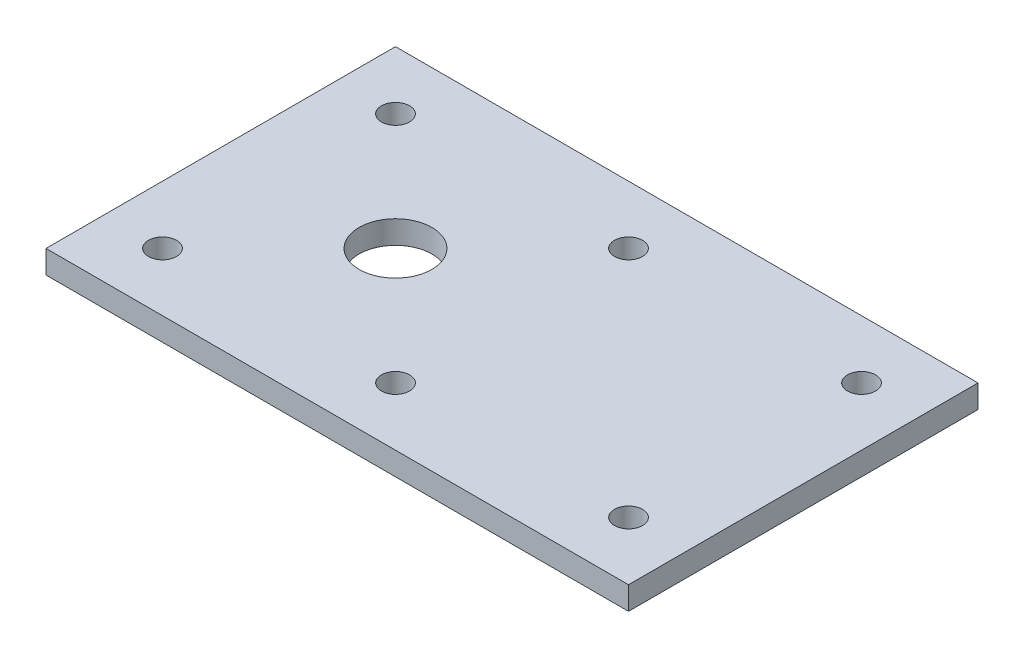
SolidWorks part; units mm, degrees
ref_plane "Front Plane" through (0, 0, 0) normal (0, 0, 1) x (1, 0, 0)
ref_plane "Top Plane" through (0, 0, 0) normal (0, 1, 0) x (1, 0, 0)
ref_plane "Right Plane" through (0, 0, 0) normal (1, 0, 0) x (0, 0, -1)
sketch "Sketch1" plane through (0, 0, 0) normal (0, 1, 0) x (1, 0, 0)
  line L0 (-60, 0) -> (140, 0) construction
  line L1 (-60, 60) -> (140, 60)
  line L2 (-60, 60) -> (-60, -60)
  line L3 (-60, -60) -> (140, -60)
  line L4 (140, 60) -> (140, -60)
  dimension "D1" = 200
  dimension "D2" = 120
  dimension "D3" = 60
extrude "Boss-Extrude1" add sketch "Sketch1" along normal blind 7.9248 contours L2 L1 L4 L3
sketch "Sketch3" plane through (0, 7.9248, 0) normal (0, 1, 0) x (1, 0, 0)
  line L0 (-60, 40) -> (-40, 40) construction
  line L1 (-60, 60) -> (-60, -60) construction
  line L2 (-40, 60) -> (-40, -60) construction
  line L3 (-60, 60) -> (140, 60) construction
  line L4 (-60, -60) -> (140, -60) construction
  line L5 (-40, 40) -> (-40, 60) construction
  line L6 (-40, 40) -> (-40, 60) construction
  line L7 (-40, 40) -> (-44.8013, 40.4875) construction
  line L8 (-40, 40) -> (-44.8152, 40.3229) construction
  circle A0 centre (-40, 40) radius 4.826
  dimension "D1" = 20
  dimension "D2" = 20
  dimension "D3" = 4.826
extrude "Cut-Extrude1" cut sketch "Sketch3" against normal through all contours A0
pattern_linear "LPattern1" count 3 spacing 80 along (1, 0, 0) count 2 spacing 80 along (0, 0, 1) of "Cut-Extrude1"
sketch "Sketch6" plane through (0, 7.9248, 0) normal (0, 1, 0) x (1, 0, 0)
  circle A0 centre (0, 0) radius 12.5
extrude "Cut-Extrude2" cut sketch "Sketch6" against normal through all contours A0
sketch "Sketch8" plane through (0, 7.9248, 0) normal (0, 1, 0) x (1, 0, 0)
